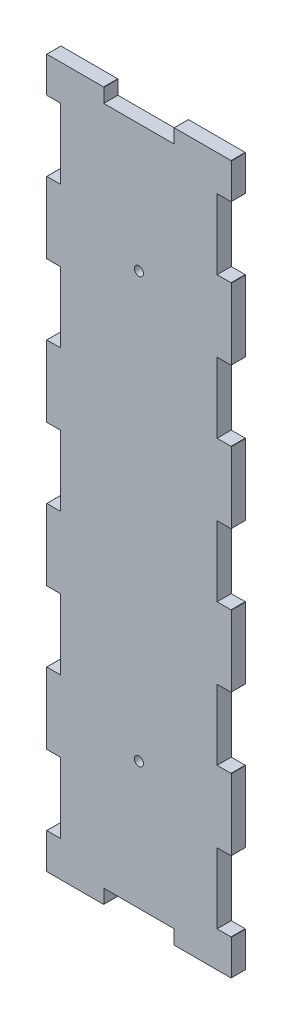
SolidWorks part; units mm, degrees
ref_plane "Front Plane" through (0, 0, 0) normal (0, 0, 1) x (1, 0, 0)
ref_plane "Top Plane" through (0, 0, 0) normal (0, 1, 0) x (1, 0, 0)
ref_plane "Right Plane" through (0, 0, 0) normal (1, 0, 0) x (0, 0, -1)
sketch "Model" plane through (0, 0, 0) normal (0, 0, 1) x (1, 0, 0)
  line L0 (-12.44, -124.95) -> (-12.43, -124.94)
  line L1 (-12.43, -124.94) -> (-12.42, -124.92)
  line L2 (-12.42, -124.92) -> (-12.41, -124.91)
  line L3 (-12.41, -124.91) -> (-12.4, -124.89)
  line L4 (-12.4, -124.89) -> (-12.4, -119.97)
  line L5 (-12.4, -119.97) -> (12.4, -119.97)
  line L6 (12.4, -119.97) -> (12.4, -124.89)
  line L7 (12.4, -124.89) -> (12.42, -124.93)
  line L8 (12.42, -124.93) -> (12.43, -124.94)
  line L9 (12.43, -124.94) -> (12.45, -124.95)
  line L10 (12.45, -124.95) -> (12.46, -124.96)
  line L11 (12.46, -124.96) -> (12.48, -124.97)
  line L12 (12.48, -124.97) -> (32.52, -124.97)
  line L13 (32.52, -124.97) -> (32.56, -124.95)
  line L14 (32.56, -124.95) -> (32.57, -124.94)
  line L15 (32.57, -124.94) -> (32.58, -124.92)
  line L16 (32.58, -124.92) -> (32.59, -124.91)
  line L17 (32.59, -124.91) -> (32.6, -124.89)
  line L18 (32.6, -124.89) -> (32.6, -112.48)
  line L19 (32.6, -112.48) -> (32.58, -112.44)
  line L20 (32.58, -112.44) -> (32.57, -112.43)
  line L21 (32.57, -112.43) -> (32.55, -112.42)
  line L22 (32.55, -112.42) -> (32.54, -112.41)
  line L23 (32.54, -112.41) -> (32.52, -112.4)
  line L24 (32.52, -112.4) -> (27.6, -112.4)
  line L25 (27.6, -112.4) -> (27.6, -87.6)
  line L26 (27.6, -87.6) -> (32.52, -87.6)
  line L27 (32.52, -87.6) -> (32.56, -87.58)
  line L28 (32.56, -87.58) -> (32.57, -87.57)
  line L29 (32.57, -87.57) -> (32.58, -87.55)
  line L30 (32.58, -87.55) -> (32.59, -87.54)
  line L31 (32.59, -87.54) -> (32.6, -87.52)
  line L32 (32.6, -87.52) -> (32.6, -62.48)
  line L33 (32.6, -62.48) -> (32.58, -62.44)
  line L34 (32.58, -62.44) -> (32.57, -62.43)
  line L35 (32.57, -62.43) -> (32.55, -62.42)
  line L36 (32.55, -62.42) -> (32.54, -62.41)
  line L37 (32.54, -62.41) -> (32.52, -62.4)
  line L38 (32.52, -62.4) -> (27.6, -62.4)
  line L39 (27.6, -62.4) -> (27.6, -37.6)
  line L40 (27.6, -37.6) -> (32.52, -37.6)
  line L41 (32.52, -37.6) -> (32.56, -37.58)
  line L42 (32.56, -37.58) -> (32.57, -37.57)
  line L43 (32.57, -37.57) -> (32.58, -37.55)
  line L44 (32.58, -37.55) -> (32.59, -37.54)
  line L45 (32.59, -37.54) -> (32.6, -37.52)
  line L46 (32.6, -37.52) -> (32.6, -12.48)
  line L47 (32.6, -12.48) -> (32.58, -12.44)
  line L48 (32.58, -12.44) -> (32.57, -12.43)
  line L49 (32.57, -12.43) -> (32.55, -12.42)
  line L50 (32.55, -12.42) -> (32.54, -12.41)
  line L51 (32.54, -12.41) -> (32.52, -12.4)
  line L52 (32.52, -12.4) -> (27.6, -12.4)
  line L53 (27.6, -12.4) -> (27.6, 12.4)
  line L54 (27.6, 12.4) -> (32.52, 12.4)
  line L55 (32.52, 12.4) -> (32.56, 12.42)
  line L56 (32.56, 12.42) -> (32.57, 12.43)
  line L57 (32.57, 12.43) -> (32.58, 12.45)
  line L58 (32.58, 12.45) -> (32.59, 12.46)
  line L59 (32.59, 12.46) -> (32.6, 12.48)
  line L60 (32.6, 12.48) -> (32.6, 37.52)
  line L61 (32.6, 37.52) -> (32.58, 37.56)
  line L62 (32.58, 37.56) -> (32.57, 37.57)
  line L63 (32.57, 37.57) -> (32.55, 37.58)
  line L64 (32.55, 37.58) -> (32.54, 37.59)
  line L65 (32.54, 37.59) -> (32.52, 37.6)
  line L66 (32.52, 37.6) -> (27.6, 37.6)
  line L67 (27.6, 37.6) -> (27.6, 62.4)
  line L68 (27.6, 62.4) -> (32.52, 62.4)
  line L69 (32.52, 62.4) -> (32.56, 62.42)
  line L70 (32.56, 62.42) -> (32.57, 62.43)
  line L71 (32.57, 62.43) -> (32.58, 62.45)
  line L72 (32.58, 62.45) -> (32.59, 62.46)
  line L73 (32.59, 62.46) -> (32.6, 62.48)
  line L74 (32.6, 62.48) -> (32.6, 87.52)
  line L75 (32.6, 87.52) -> (32.58, 87.56)
  line L76 (32.58, 87.56) -> (32.57, 87.57)
  line L77 (32.57, 87.57) -> (32.55, 87.58)
  line L78 (32.55, 87.58) -> (32.54, 87.59)
  line L79 (32.54, 87.59) -> (32.52, 87.6)
  line L80 (32.52, 87.6) -> (27.6, 87.6)
  line L81 (27.6, 87.6) -> (27.6, 112.4)
  line L82 (27.6, 112.4) -> (32.52, 112.4)
  line L83 (32.52, 112.4) -> (32.56, 112.42)
  line L84 (32.56, 112.42) -> (32.57, 112.43)
  line L85 (32.57, 112.43) -> (32.58, 112.45)
  line L86 (32.58, 112.45) -> (32.59, 112.46)
  line L87 (32.59, 112.46) -> (32.6, 112.48)
  line L88 (32.6, 112.48) -> (32.6, 124.89)
  line L89 (32.6, 124.89) -> (32.58, 124.93)
  line L90 (32.58, 124.93) -> (32.57, 124.94)
  line L91 (32.57, 124.94) -> (32.55, 124.95)
  line L92 (32.55, 124.95) -> (32.54, 124.96)
  line L93 (32.54, 124.96) -> (32.52, 124.97)
  line L94 (32.52, 124.97) -> (12.48, 124.97)
  line L95 (12.48, 124.97) -> (12.44, 124.95)
  line L96 (12.44, 124.95) -> (12.43, 124.94)
  line L97 (12.43, 124.94) -> (12.42, 124.92)
  line L98 (12.42, 124.92) -> (12.41, 124.91)
  line L99 (12.41, 124.91) -> (12.4, 124.89)
  line L100 (12.4, 124.89) -> (12.4, 119.97)
  line L101 (12.4, 119.97) -> (-12.4, 119.97)
  line L102 (-12.4, 119.97) -> (-12.4, 124.89)
  line L103 (-12.4, 124.89) -> (-12.42, 124.93)
  line L104 (-12.42, 124.93) -> (-12.43, 124.94)
  line L105 (-12.43, 124.94) -> (-12.45, 124.95)
  line L106 (-12.45, 124.95) -> (-12.46, 124.96)
  line L107 (-12.46, 124.96) -> (-12.48, 124.97)
  line L108 (-12.48, 124.97) -> (-32.52, 124.97)
  line L109 (-32.52, 124.97) -> (-32.56, 124.95)
  line L110 (-32.56, 124.95) -> (-32.57, 124.94)
  line L111 (-32.57, 124.94) -> (-32.58, 124.92)
  line L112 (-32.58, 124.92) -> (-32.59, 124.91)
  line L113 (-32.59, 124.91) -> (-32.6, 124.89)
  line L114 (-32.6, 124.89) -> (-32.6, 112.48)
  line L115 (-32.6, 112.48) -> (-32.58, 112.44)
  line L116 (-32.58, 112.44) -> (-32.57, 112.43)
  line L117 (-32.57, 112.43) -> (-32.55, 112.42)
  line L118 (-32.55, 112.42) -> (-32.54, 112.41)
  line L119 (-32.54, 112.41) -> (-32.52, 112.4)
  line L120 (-32.52, 112.4) -> (-27.6, 112.4)
  line L121 (-27.6, 112.4) -> (-27.6, 87.6)
  line L122 (-27.6, 87.6) -> (-32.52, 87.6)
  line L123 (-32.52, 87.6) -> (-32.56, 87.58)
  line L124 (-32.56, 87.58) -> (-32.57, 87.57)
  line L125 (-32.57, 87.57) -> (-32.58, 87.55)
  line L126 (-32.58, 87.55) -> (-32.59, 87.54)
  line L127 (-32.59, 87.54) -> (-32.6, 87.52)
  line L128 (-32.6, 87.52) -> (-32.6, 62.48)
  line L129 (-32.6, 62.48) -> (-32.58, 62.44)
  line L130 (-32.58, 62.44) -> (-32.57, 62.43)
  line L131 (-32.57, 62.43) -> (-32.55, 62.42)
  line L132 (-32.55, 62.42) -> (-32.54, 62.41)
  line L133 (-32.54, 62.41) -> (-32.52, 62.4)
  line L134 (-32.52, 62.4) -> (-27.6, 62.4)
  line L135 (-27.6, 62.4) -> (-27.6, 37.6)
  line L136 (-27.6, 37.6) -> (-32.52, 37.6)
  line L137 (-32.52, 37.6) -> (-32.56, 37.58)
  line L138 (-32.56, 37.58) -> (-32.57, 37.57)
  line L139 (-32.57, 37.57) -> (-32.58, 37.55)
  line L140 (-32.58, 37.55) -> (-32.59, 37.54)
  line L141 (-32.59, 37.54) -> (-32.6, 37.52)
  line L142 (-32.6, 37.52) -> (-32.6, 12.48)
  line L143 (-32.6, 12.48) -> (-32.58, 12.44)
  line L144 (-32.58, 12.44) -> (-32.57, 12.43)
  line L145 (-32.57, 12.43) -> (-32.55, 12.42)
  line L146 (-32.55, 12.42) -> (-32.54, 12.41)
  line L147 (-32.54, 12.41) -> (-32.52, 12.4)
  line L148 (-32.52, 12.4) -> (-27.6, 12.4)
  line L149 (-27.6, 12.4) -> (-27.6, -12.4)
  line L150 (-27.6, -12.4) -> (-32.52, -12.4)
  line L151 (-32.52, -12.4) -> (-32.56, -12.42)
  line L152 (-32.56, -12.42) -> (-32.57, -12.43)
  line L153 (-32.57, -12.43) -> (-32.58, -12.45)
  line L154 (-32.58, -12.45) -> (-32.59, -12.46)
  line L155 (-32.59, -12.46) -> (-32.6, -12.48)
  line L156 (-32.6, -12.48) -> (-32.6, -37.52)
  line L157 (-32.6, -37.52) -> (-32.58, -37.56)
  line L158 (-32.58, -37.56) -> (-32.57, -37.57)
  line L159 (-32.57, -37.57) -> (-32.55, -37.58)
  line L160 (-32.55, -37.58) -> (-32.54, -37.59)
  line L161 (-32.54, -37.59) -> (-32.52, -37.6)
  line L162 (-32.52, -37.6) -> (-27.6, -37.6)
  line L163 (-27.6, -37.6) -> (-27.6, -62.4)
  line L164 (-27.6, -62.4) -> (-32.52, -62.4)
  line L165 (-32.52, -62.4) -> (-32.56, -62.42)
  line L166 (-32.56, -62.42) -> (-32.57, -62.43)
  line L167 (-32.57, -62.43) -> (-32.58, -62.45)
  line L168 (-32.58, -62.45) -> (-32.59, -62.46)
  line L169 (-32.59, -62.46) -> (-32.6, -62.48)
  line L170 (-32.6, -62.48) -> (-32.6, -87.52)
  line L171 (-32.6, -87.52) -> (-32.58, -87.56)
  line L172 (-32.58, -87.56) -> (-32.57, -87.57)
  line L173 (-32.57, -87.57) -> (-32.55, -87.58)
  line L174 (-32.55, -87.58) -> (-32.54, -87.59)
  line L175 (-32.54, -87.59) -> (-32.52, -87.6)
  line L176 (-32.52, -87.6) -> (-27.6, -87.6)
  line L177 (-27.6, -87.6) -> (-27.6, -112.4)
  line L178 (-27.6, -112.4) -> (-32.52, -112.4)
  line L179 (-32.52, -112.4) -> (-32.56, -112.42)
  line L180 (-32.56, -112.42) -> (-32.57, -112.43)
  line L181 (-32.57, -112.43) -> (-32.58, -112.45)
  line L182 (-32.58, -112.45) -> (-32.59, -112.46)
  line L183 (-32.59, -112.46) -> (-32.6, -112.48)
  line L184 (-32.6, -112.48) -> (-32.6, -124.89)
  line L185 (-32.6, -124.89) -> (-32.58, -124.93)
  line L186 (-32.58, -124.93) -> (-32.57, -124.94)
  line L187 (-32.57, -124.94) -> (-32.55, -124.95)
  line L188 (-32.55, -124.95) -> (-32.54, -124.96)
  line L189 (-32.54, -124.96) -> (-32.52, -124.97)
  line L190 (-32.52, -124.97) -> (-12.48, -124.97)
  line L191 (-12.48, -124.97) -> (-12.44, -124.95)
extrude "Boss-Extrude1" add sketch "Model" along normal blind 5
sketch "Sketch1" plane through (0, 0, 5) normal (0, 0, 1) x (1, 0, 0)
  line L0 (-12.4, -119.97) -> (12.4, -119.97) construction
  line L1 (-27.6, 119.97) -> (27.6, 119.97) construction
  line L2 (-27.6, 119.97) -> (-27.6, -119.97) construction
  line L3 (-27.6, -119.97) -> (27.6, -119.97) construction
  line L4 (27.6, 119.97) -> (27.6, -119.97) construction
  line L5 (-27.6, 119.97) -> (27.6, -119.97) construction
  line L6 (-27.6, -119.97) -> (27.6, 119.97) construction
  line L7 (27.6, -112.4) -> (27.6, -87.6) construction
  line L8 (-27.6, 0) -> (27.6, 0) construction
  circle A0 centre (0, 74.935) radius 1.6
  circle A1 centre (0, -74.935) radius 1.6
  point P4 (0, 0)
  dimension "D1" = 3.2
  dimension "D2" = 149.87
extrude "Cut-Extrude2" cut sketch "Sketch1" against normal through all
